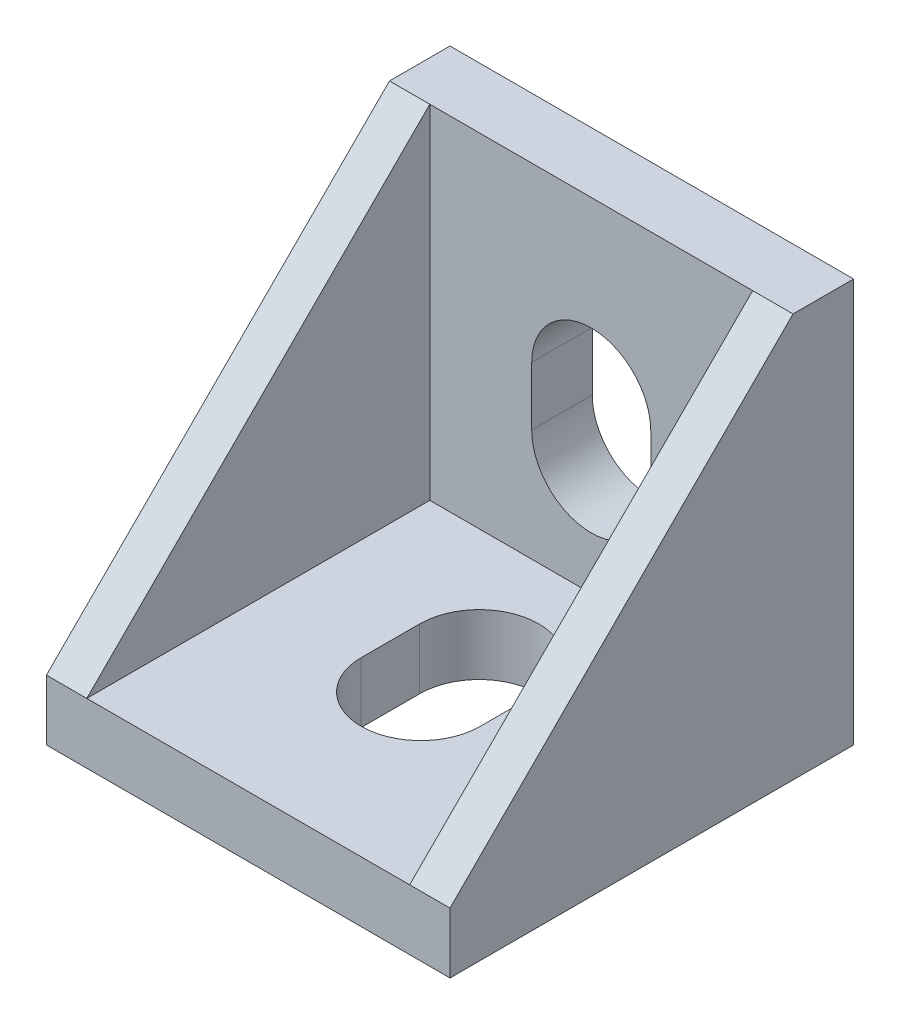
SolidWorks part; units mm, degrees
ref_plane "前视基准面" through (0, 0, 0) normal (0, 0, 1) x (1, 0, 0)
ref_plane "上视基准面" through (0, 0, 0) normal (0, 1, 0) x (1, 0, 0)
ref_plane "右视基准面" through (0, 0, 0) normal (1, 0, 0) x (0, 0, -1)
sketch "Sketch1" plane through (0, 0, 0) normal (0, 1, 0) x (1, 0, 0)
  line L1 (-10, -10) -> (10, -10)
  line L2 (-10, -10) -> (-10, 10)
  line L3 (-10, 10) -> (10, 10)
  line L4 (10, -10) -> (10, 10)
  line L5 (-10, -10) -> (10, 10) construction
  line L6 (-10, 10) -> (10, -10) construction
  line L7 (-2.95, -1.45) -> (2.95, -1.45) construction
  line L8 (-2.95, -1.45) -> (-2.95, 1.45)
  line L9 (-2.95, 1.45) -> (2.95, 1.45) construction
  line L10 (2.95, -1.45) -> (2.95, 1.45)
  line L11 (-2.95, -1.45) -> (2.95, 1.45) construction
  line L12 (-2.95, 1.45) -> (2.95, -1.45) construction
  arc A0 (2.95, 1.45) -> (-2.95, 1.45) centre (0, 1.45) ccw
  arc A1 (2.95, -1.45) -> (-2.95, -1.45) centre (0, -1.45) cw
  point P0 (0, 0)
  point P6 (0, 0)
  dimension "D3" = 8.8
  dimension "D1" = 20
  dimension "D2" = 20
  dimension "D4" = 5.9
extrude "Boss-Extrude1" add sketch "Sketch1" along normal blind 3
sketch "Sketch2" plane through (0, 0, -10) normal (0, 0, -1) x (-1, 0, 0)
  line L0 (-10, 0) -> (10, 0)
  line L1 (-10, 0) -> (-10, 20)
  line L2 (-10, 20) -> (10, 20)
  line L3 (10, 0) -> (10, 20)
  line L4 (-10, 0) -> (10, 20) construction
  line L5 (-10, 20) -> (10, 0) construction
  line L6 (-2.95, 8.55) -> (2.95, 8.55) construction
  line L7 (-2.95, 8.55) -> (-2.95, 11.45)
  line L8 (-2.95, 11.45) -> (2.95, 11.45) construction
  line L9 (2.95, 8.55) -> (2.95, 11.45)
  line L10 (-2.95, 8.55) -> (2.95, 11.45) construction
  line L11 (-2.95, 11.45) -> (2.95, 8.55) construction
  arc A0 (2.95, 11.45) -> (-2.95, 11.45) centre (0, 11.45) ccw
  arc A1 (2.95, 8.55) -> (-2.95, 8.55) centre (0, 8.55) cw
  point P0 (0, 10)
  point P5 (0, 10)
  point P12 (0, 0)
  point P14 (0, 0)
  dimension "D1" = 20
  dimension "D2" = 8.8
  dimension "D3" = 5.9
  dimension "D4" = 20
extrude "Boss-Extrude2" add sketch "Sketch2" against normal blind 3
sketch "Sketch3" plane through (10, 0, 0) normal (1, 0, 0) x (0, 0, -1)
  line L0 (7, 20) -> (-10, 3)
  line L1 (7, 20) -> (7, 3)
  line L2 (7, 3) -> (-10, 3)
extrude "Boss-Extrude3" add sketch "Sketch3" against normal blind 2
sketch "Sketch4" plane through (-10, 0, 0) normal (-1, 0, 0) x (0, 0, 1)
  line L3 (-7, 20) -> (-7, 3)
  line L4 (-7, 3) -> (10, 3)
  line L5 (10, 3) -> (-7, 20)
  line L6 (-7, 20) -> (-7, 3)
  line L7 (-7, 3) -> (10, 3)
  line L8 (10, 3) -> (-7, 20)
  dimension "D1" = 0
extrude "Boss-Extrude4" add sketch "Sketch4" against normal blind 2
